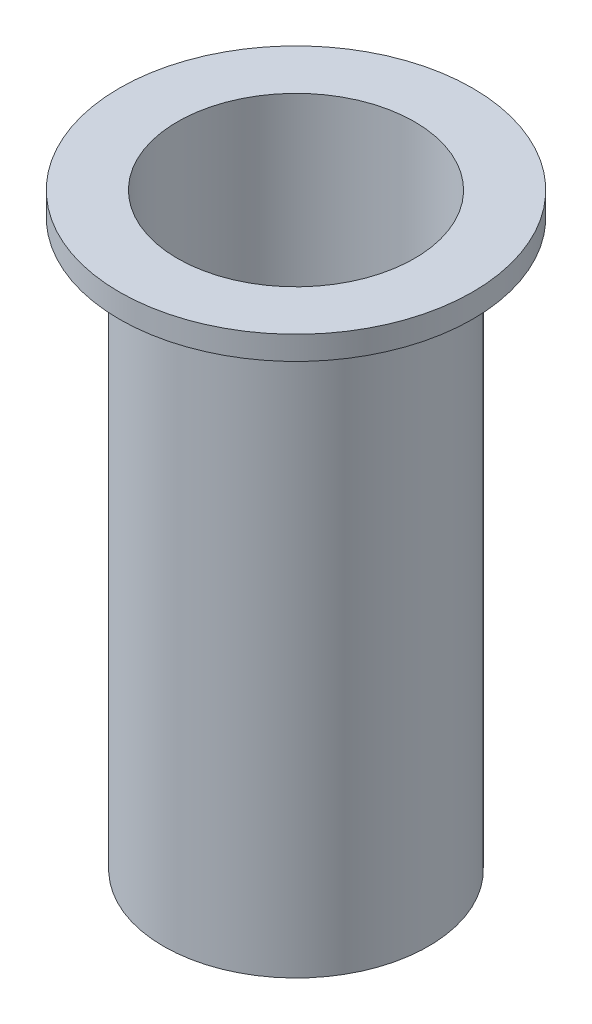
SolidWorks part; units mm, degrees
material "AISI 304"
ref_plane "Front Plane" through (0, 0, 0) normal (0, 0, 1) x (1, 0, 0)
ref_plane "Top Plane" through (0, 0, 0) normal (0, 1, 0) x (1, 0, 0)
ref_plane "Right Plane" through (0, 0, 0) normal (1, 0, 0) x (0, 0, -1)
sketch "Shell Profile" plane through (0, 0, 0) normal (0, 0, 1) x (1, 0, 0)
  line L0 (51.1302, 0) -> (51.1302, 254)
  line L1 (51.1302, 0) -> (57.15, 0)
  line L2 (57.15, 0) -> (57.15, 243.84)
  line L3 (57.15, 243.84) -> (76.2, 243.84)
  line L4 (76.2, 243.84) -> (76.2, 254)
  line L5 (76.2, 254) -> (51.1302, 254)
  line L6 (0, 0) -> (0, -75688.6337) construction
  dimension "Outer Flange Diameter" = 152.4
  dimension "Flange Thickness" = 10.16
  dimension "Pipe Outer Diameter" = 114.3
  dimension "Pipe Thickness" = 6.0198
  dimension "Pipe Length" = 254
revolve "Shell Revolve" add sketch "Shell Profile" angle 360 about L6
